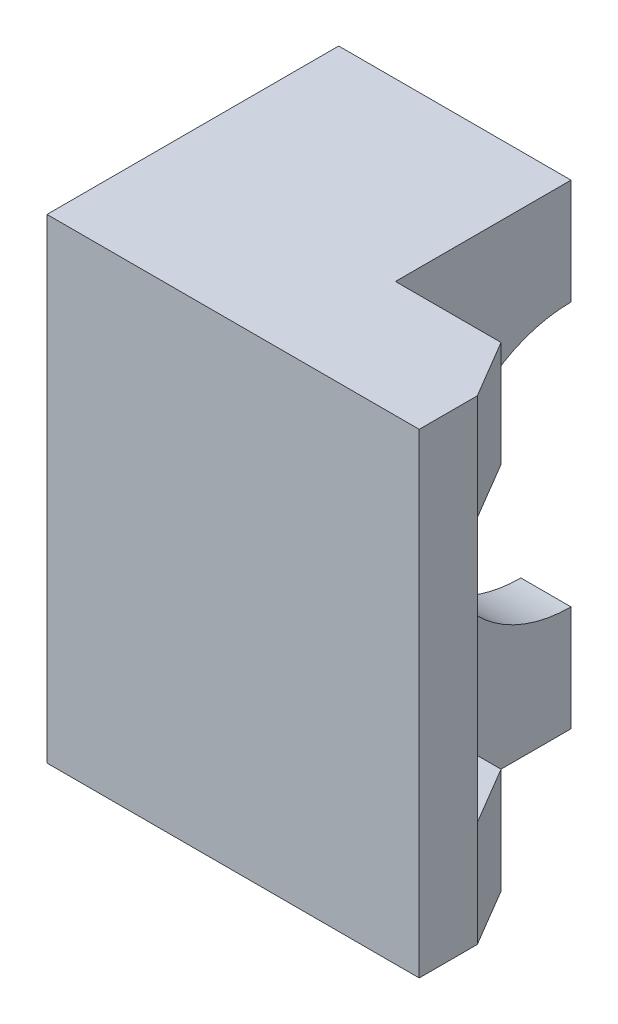
SolidWorks part; units mm, degrees
ref_plane "Front Plane" through (0, 0, 0) normal (0, 0, 1) x (1, 0, 0)
ref_plane "Top Plane" through (0, 0, 0) normal (0, 1, 0) x (1, 0, 0)
ref_plane "Right Plane" through (0, 0, 0) normal (1, 0, 0) x (0, 0, -1)
sketch "Sketch1" plane through (0, 0, 0) normal (0, 1, 0) x (1, 0, 0)
  line L0 (0, 0) -> (70.5, 0)
  line L1 (70.5, 0) -> (70.5, 11)
  line L2 (70.5, 11) -> (64, 22)
  line L3 (64, 22) -> (44, 22)
  line L4 (44, 22) -> (44, 55.25)
  line L5 (44, 55.25) -> (0, 55.25)
  line L6 (0, 55.25) -> (0, 0)
  dimension "D1" = 55.25
  dimension "D2" = 70.5
  dimension "D3" = 44
  dimension "D4" = 20
  dimension "D5" = 11
  dimension "D6" = 33.25
extrude "Boss-Extrude1" add sketch "Sketch1" along normal blind 90 contours L5 L6 L0 L1 L2 L3 L4
sketch "Sketch7" plane through (44, 0, 0) normal (1, 0, 0) x (0, 0, -1)
  line L1 (22, 0) -> (55.25, 0) construction
  line L2 (55.25, 90) -> (55.25, 0) construction
  arc A1 (55.25, 20) -> (55.25, 70) centre (55.25, 45) cw
  dimension "D1" = 25
  dimension "D2" = 45
  dimension "D4" = 20
extrude "Cut-Extrude6" cut sketch "Sketch7" against normal blind 44 and the other way through all flip side to cut
sketch "Sketch8" plane through (0, 0, -55.25) normal (0, 0, -1) x (-1, 0, 0)
  line L0 (-44, 90) -> (0, 90) construction
  line L1 (-44, 90) -> (-44, 0) construction
  line L2 (-44, 0) -> (0, 0) construction
  line L4 (-34.5, 78.5) -> (-34.5, 63.5)
  line L5 (-34.5, 78.5) -> (-9.5, 78.5)
  line L6 (-9.5, 78.5) -> (-9.5, 63.5)
  line L7 (-9.5, 63.5) -> (-34.5, 63.5)
  line L9 (-9.5, 11.5) -> (-9.5, 26.5)
  line L10 (-34.5, 11.5) -> (-9.5, 11.5)
  line L11 (-34.5, 11.5) -> (-34.5, 26.5)
  line L12 (-9.5, 26.5) -> (-34.5, 26.5)
  line L13 (0, 20) -> (0, 0) construction
  dimension "D1" = 11.5
  dimension "D2" = 9.5
  dimension "D3" = 15
  dimension "D4" = 25
  dimension "D5" = 11.5
  dimension "D6" = 9.5
extrude "Cut-Extrude9" cut sketch "Sketch8" against normal blind 15 contours L7 L4 L5 L6 | L10 L9 L12 L11
sketch "Sketch13" plane through (0, 0, -22) normal (0, 0, -1) x (-1, 0, 0)
  line L0 (-70.5, 70) -> (-70.5, 20)
  line L1 (-70.5, 90) -> (-70.5, 0) construction
  line L2 (-70.5, 70) -> (-54, 70)
  line L3 (-54, 70) -> (-54, 20)
  line L4 (-54, 20) -> (-70.5, 20)
  line L5 (-64, 90) -> (-44, 90) construction
  dimension "D1" = 20
  dimension "D2" = 50
  dimension "D3" = 16.5
extrude "Cut-Extrude18" cut sketch "Sketch13" against normal blind 11 contours L2 L3 L4 L0
